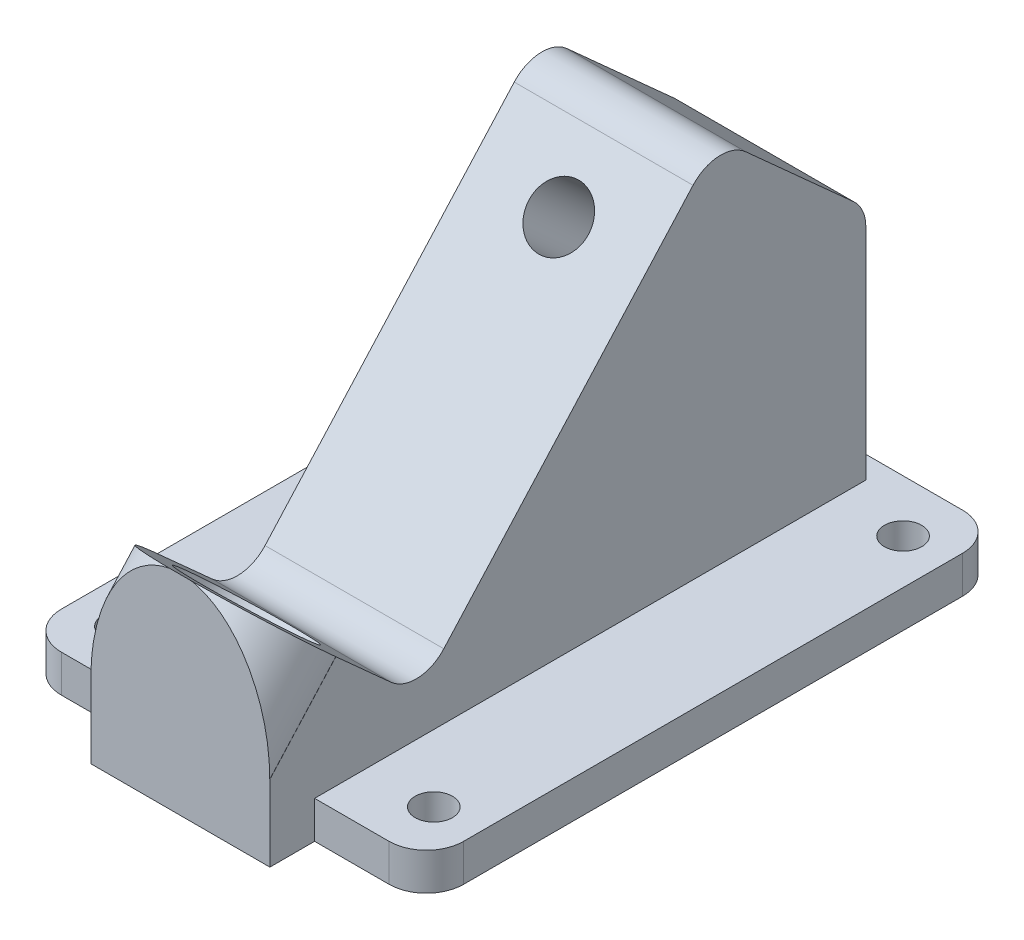
SolidWorks part; units mm, degrees
material "6063-O"
ref_plane "Front Plane" through (0, 0, 0) normal (0, 0, 1) x (1, 0, 0)
ref_plane "Top Plane" through (0, 0, 0) normal (0, 1, 0) x (1, 0, 0)
ref_plane "Right Plane" through (0, 0, 0) normal (1, 0, 0) x (0, 0, -1)
sketch "Sketch1" plane through (0, 0, 0) normal (0, 1, 0) x (1, 0, 0)
  line L1 (-27, -38.5) -> (27, -38.5)
  line L2 (-27, -38.5) -> (-27, 38.5)
  line L3 (-27, 38.5) -> (27, 38.5)
  line L4 (27, -38.5) -> (27, 38.5)
  line L5 (-27, -38.5) -> (27, 38.5) construction
  line L6 (-27, 38.5) -> (27, -38.5) construction
  point P0 (0, 0)
  dimension "D1" = 54
  dimension "D2" = 77
extrude "Boss-Extrude1" add sketch "Sketch1" along normal blind 5
sketch "Sketch3" plane through (0, 5, 0) normal (0, 1, 0) x (1, 0, 0)
  line L0 (-27, -4.5) -> (27, -4.5) construction
  line L1 (-12, 35.5) -> (12, 35.5)
  line L2 (-12, 35.5) -> (-12, -44.5)
  line L3 (-12, -44.5) -> (12, -44.5)
  line L4 (12, 35.5) -> (12, -44.5)
  line L5 (-12, 35.5) -> (12, -44.5) construction
  line L6 (-12, -44.5) -> (12, 35.5) construction
  line L8 (-27, -38.5) -> (27, -38.5) construction
  line L9 (-27, 38.5) -> (-27, -38.5) construction
  line L10 (27, -38.5) -> (27, 38.5) construction
  point P0 (0, -4.5)
  dimension "D1" = 24
  dimension "D2" = 80
  dimension "D3" = 34
extrude "Boss-Extrude2" add sketch "Sketch3" along normal blind 60 and the other way up to surface other way up to face at (0, 0, 0)
sketch "Sketch7" plane through (12, 0, 0) normal (1, 0, 0) x (0, 0, -1)
  line L0 (-46.7943, 30.0739) -> (-24.5, 10)
  line L1 (-24.5, 10) -> (15.6478, 54.5887)
  line L2 (15.6478, 54.5887) -> (50.5, 23.2077)
  line L3 (-38.5, 5) -> (35.5, 5) construction
  line L4 (-44.5, 65) -> (-44.5, 0) construction
  line L5 (50.5, 23.2077) -> (50.5, 70)
  line L6 (-46.7943, 30.0739) -> (-49.5, 27.069)
  line L7 (-49.5, 27.069) -> (-49.5, 70)
  line L8 (-49.5, 70) -> (50.5, 70)
  line L9 (-38.5, 5) -> (38.5, 5) construction
  line L10 (-44.5, 65) -> (-44.5, 0) construction
  dimension "D1" = 48
  dimension "D2" = 20
  dimension "D3" = 5
  dimension "D4" = 30
  dimension "D5" = 60
  dimension "D6" = 100
  dimension "D7" = 5
  dimension "D8" = 65
  dimension "D9" = 90
extrude "Cut-Extrude5" cut sketch "Sketch7" against normal through all
sketch "Sketch8" plane through (0, -6.6603, 5.9969) normal (0, 0.7431, -0.6691) x (1, 0, 0)
  line L0 (0, -51.811) -> (0, -24.8984) construction
  line L1 (-12, -24.8984) -> (12, -24.8984) construction
  line L2 (12, -51.811) -> (-12, -51.811) construction
  line L3 (0, -47.8984) -> (0, -31.8984)
  arc A0 (0, -47.8984) -> (0, -31.8984) centre (0, -39.8984) ccw
  dimension "D1" = 16
  dimension "D3" = 15
sketch "Sketch9" plane through (0, 16.6603, 18.5031) normal (0, 0.6691, 0.7431) x (1, 0, 0)
  line L0 (-12, -8.9623) -> (12, -8.9623) construction
  line L1 (12, -8.9623) -> (12, 51.0377) construction
  circle A0 centre (0, 37.0377) radius 4
  dimension "D1" = 8
  dimension "D2" = 46
  dimension "D3" = 12
extrude "Cut-Extrude7" cut sketch "Sketch9" against normal through all
fillet "Fillet4" radius 5 3 edges at (0, 54.5887, -15.6478) (0, 36.7137, -35.5) (0, 10, 24.5)
ref_plane "Plane1" through (0, -13.4506, -14.9384) normal (0, 0.6691, 0.7431) x (1, 0, 0)
sketch "Sketch10" plane through (0, -13.4506, -14.9384) normal (0, 0.6691, 0.7431) x (1, 0, 0)
  circle A0 centre (0, 37.0377) radius 7.5
  circle A1 centre (0, 37.0377) radius 4 construction
  circle A2 centre (0, 37.0377) radius 4 construction
  dimension "D1" = 15
extrude "Cut-Extrude8" cut sketch "Sketch10" along normal blind 20
sketch "Sketch11" plane through (0, 0, 0) normal (0, -1, 0) x (1, 0, 0)
  line L1 (21, 31.5) -> (-21, 31.5) construction
  line L2 (21, 31.5) -> (21, -31.5) construction
  line L3 (21, -31.5) -> (-21, -31.5) construction
  line L4 (-21, 31.5) -> (-21, -31.5) construction
  line L5 (21, 31.5) -> (-21, -31.5) construction
  line L6 (21, -31.5) -> (-21, 31.5) construction
  point P0 (0, 0)
  dimension "D1" = 42
  dimension "D2" = 63
hole_wizard "Ø5.0 (5) Diameter Hole1" positions "3DSketch1" profile "Sketch12" hole size "Ø5.0" standard "DIN" end condition through all
sketch3d "3DSketch1"
  point P0 (21, 0, -31.5)
  point P3 (-21, 0, -31.5)
  point P6 (-21, 0, 31.5)
  point P9 (21, 0, 31.5)
sketch "Sketch12" plane through (21, 0, -31.5) normal (1, 0, 0) x (0, 0, -1)
  line L0 (0, 0) -> (0, 52.5273)
  line L1 (0, 52.5273) -> (2.5, 52.5273)
  line L2 (2.5, 52.5273) -> (2.5, 0)
  line L5 (2.5, 0) -> (0, 0)
  line L11 (0, -6.35) -> (0, 107.95) construction
  dimension "Thru Hole Dia." = 5
  dimension "Thru Hole Depth" = 52.5273
fillet "Fillet7" radius 5 4 edges at (-27, 2.5, 38.5) (-27, 2.5, -38.5) (27, 2.5, -38.5) (27, 2.5, 38.5)
revolve "Cut-Revolve4" cut sketch "Sketch8" angle 360 about L0
sketch "Sketch13" plane through (0, -6.6603, 5.9969) normal (0, 0.7431, -0.6691) x (1, 0, 0)
  line L1 (-12.0187, -39.8984) -> (-15.5998, -39.8984)
  line L2 (-15.5998, -39.8984) -> (-15.5998, -55.3637)
  line L3 (-15.5998, -55.3637) -> (15.5998, -55.3637)
  line L4 (15.5998, -55.3637) -> (15.5998, -39.8984)
  line L5 (15.5998, -39.8984) -> (11.9813, -39.8984)
  line L7 (-12, -51.811) -> (12, -51.811) construction
  line L8 (0, -55.3637) -> (0, -29.8984) construction
  line L9 (12, -29.8984) -> (-12, -29.8984) construction
  arc A0 (-12.0187, -39.8984) -> (11.9813, -39.8984) centre (-0.0187, -39.8984) ccw
  dimension "D1" = 12
  dimension "D2" = 31.1997
  dimension "D3" = 15.4654
  dimension "D4" = 3.5812
  dimension "D6" = 3.5527
extrude "Cut-Extrude9" cut sketch "Sketch13" against normal through all
